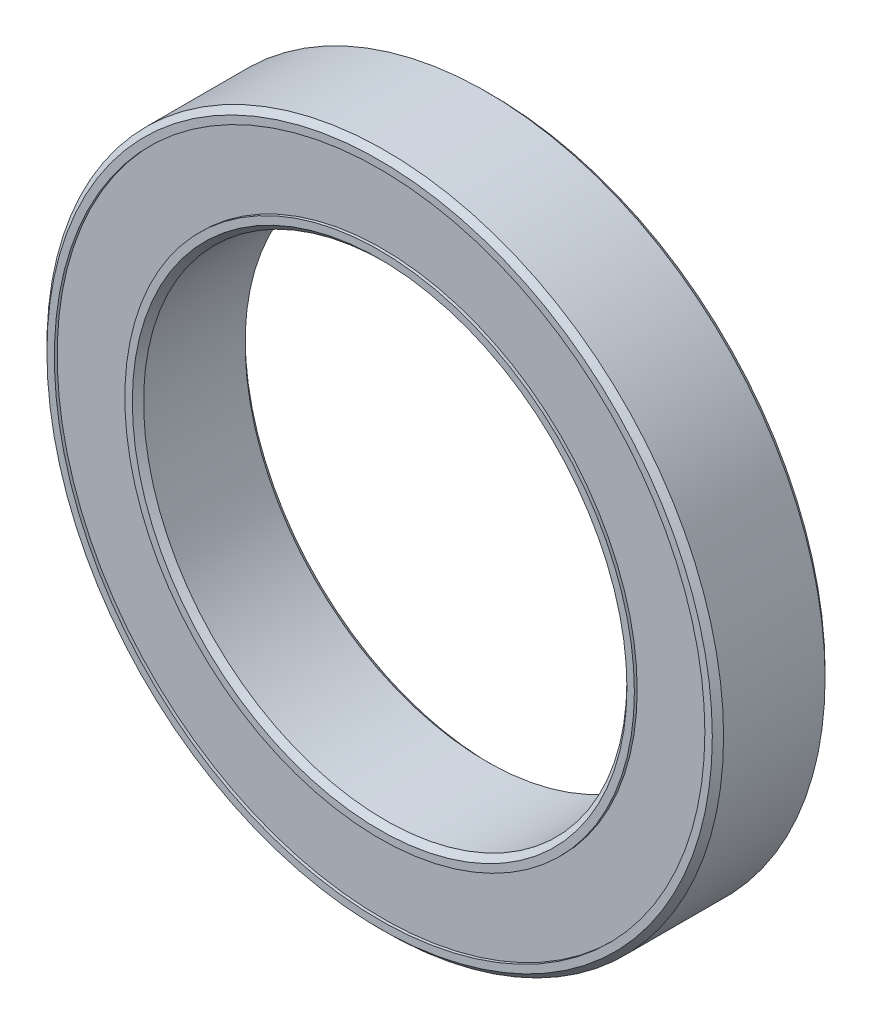
SolidWorks part; units mm, degrees
ref_plane "Front Plane" through (0, 0, 0) normal (0, 0, 1) x (1, 0, 0)
ref_plane "Top Plane" through (0, 0, 0) normal (0, 1, 0) x (1, 0, 0)
ref_plane "Right Plane" through (0, 0, 0) normal (1, 0, 0) x (0, 0, -1)
sketch "Sketch1" plane through (0, 0, 0) normal (0, 0, 1) x (1, 0, 0)
  circle A0 centre (0, 0) radius 21 construction
  circle A1 centre (0, 0) radius 14.9995 construction
  dimension "OD" = 42
  dimension "ID" = 29.999
sketch "Sketch2" plane through (0, 0, 0) normal (1, 0, 0) x (0, 0, -1)
  line L0 (-3.5, 0) -> (3.5, 0) construction
  line L1 (0, 21) -> (0, -21) construction
  line L2 (3.15, 21) -> (-3.15, 21) construction
  line L3 (-3.15, 21) -> (-3.5, 20.65) construction
  line L4 (-3.5, 20.65) -> (-3.5, 20.1872) construction
  line L5 (-3.5, 20.1872) -> (-1.5556, 20.1872) construction
  line L6 (3.5, 20.1872) -> (1.5556, 20.1872) construction
  line L7 (3.5, 20.65) -> (3.5, 20.1872) construction
  line L8 (3.15, 21) -> (3.5, 20.65) construction
  line L9 (0, 21) -> (0, 17.9998) construction
  line L10 (0, 17.9998) -> (0, 14.9995) construction
  line L11 (3.5, 17.9998) -> (-3.5, 17.9998) construction
  line L12 (-3.5, 15.3495) -> (-3.5, 15.8123) construction
  line L13 (-3.15, 14.9995) -> (-3.5, 15.3495) construction
  line L14 (3.15, 14.9995) -> (-3.15, 14.9995) construction
  line L15 (3.15, 14.9995) -> (3.5, 15.3495) construction
  line L16 (3.5, 15.3495) -> (3.5, 15.8123) construction
  line L17 (3.5, 15.8123) -> (1.5556, 15.8123) construction
  line L18 (-3.5, 15.8123) -> (-1.5556, 15.8123) construction
  line L19 (-3.5, 15) -> (-3.5, -15) construction
  line L20 (3.5, 21) -> (3.5, -21) construction
  arc A0 (-1.5556, 20.1872) -> (1.5556, 20.1872) centre (0, 17.9998) cw construction
  arc A1 (-1.5556, 15.8123) -> (1.5556, 15.8123) centre (0, 17.9998) ccw construction
  point P14 (0, 14.9995)
  point P18 (0, 17.9998)
  dimension "Approx. Ball Dia." = 5.3684
  dimension "D1" = 45
  dimension "D2" = 0.35
  dimension "D3" = 3.1111
  dimension "D4" = 2.1875
  dimension "Width" = 7
  dimension "For Shaft Diameter" = 30
  dimension "For Housing ID" = 42
sketch "Sketch3" plane through (0, 0, 0) normal (1, 0, 0) x (0, 0, -1)
  line L0 (-3.5, 20.65) -> (-3.5, 20.1872) construction
  line L1 (-3.15, 21) -> (-3.5, 20.65) construction
  line L2 (3.15, 21) -> (-3.15, 21) construction
  line L3 (3.15, 21) -> (3.5, 20.65) construction
  line L4 (3.5, 20.65) -> (3.5, 20.1872) construction
  line L5 (3.5, 20.1872) -> (1.5556, 20.1872) construction
  line L6 (-3.5, 20.1872) -> (-1.5556, 20.1872) construction
  line L7 (-3.5, 20.65) -> (-3.5, 20.1872)
  line L8 (-3.15, 21) -> (-3.5, 20.65)
  line L9 (3.15, 21) -> (-3.15, 21)
  line L10 (3.15, 21) -> (3.5, 20.65)
  line L11 (3.5, 20.65) -> (3.5, 20.1872)
  line L12 (3.5, 20.1872) -> (1.5556, 20.1872)
  line L13 (-3.5, 20.1872) -> (-1.5556, 20.1872)
  line L14 (-3.5, 15.3495) -> (-3.5, 15.8123) construction
  line L15 (-3.15, 14.9995) -> (-3.5, 15.3495) construction
  line L16 (3.15, 14.9995) -> (-3.15, 14.9995) construction
  line L17 (3.15, 14.9995) -> (3.5, 15.3495) construction
  line L18 (3.5, 15.3495) -> (3.5, 15.8123) construction
  line L19 (3.5, 15.8123) -> (1.5556, 15.8123) construction
  line L20 (-3.5, 15.8123) -> (-1.5556, 15.8123) construction
  line L21 (-3.5, 15.3495) -> (-3.5, 15.8123)
  line L22 (-3.15, 14.9995) -> (-3.5, 15.3495)
  line L23 (3.15, 14.9995) -> (-3.15, 14.9995)
  line L24 (3.15, 14.9995) -> (3.5, 15.3495)
  line L25 (3.5, 15.3495) -> (3.5, 15.8123)
  line L26 (3.5, 15.8123) -> (1.5556, 15.8123)
  line L27 (-3.5, 15.8123) -> (-1.5556, 15.8123)
  arc A0 (1.5556, 20.1872) -> (-1.5556, 20.1872) centre (0, 17.9998) ccw construction
  arc A1 (1.5556, 20.1872) -> (-1.5556, 20.1872) centre (0, 17.9998) ccw
  arc A2 (-1.5556, 15.8123) -> (1.5556, 15.8123) centre (0, 17.9998) ccw construction
  arc A3 (-1.5556, 15.8123) -> (1.5556, 15.8123) centre (0, 17.9998) ccw
revolve "Revolve1" add sketch "Sketch3" angle 360 about L0
sketch "Sketch4" plane through (0, 0, 0) normal (1, 0, 0) x (0, 0, -1)
  line L0 (-2.6842, 17.9998) -> (2.6842, 17.9998)
  arc A2 (-2.6842, 17.9998) -> (2.6842, 17.9998) centre (0, 17.9998) cw
  arc A3 (1.5556, 20.1872) -> (-1.5556, 20.1872) centre (0, 17.9998) ccw construction
revolve "Revolve2" add sketch "Sketch4" angle 360 about L0
pattern_circular "CirPattern1" count 12 over 360 about axis through (0, 0, 0) along (0, 0, 1) of bodies 104
sketch "Sketch5" plane through (0, 0, 0) normal (1, 0, 0) x (0, 0, -1)
  line L0 (-3.5, 20.1872) -> (-1.5556, 20.1872) construction
  line L1 (-3.325, 20.1872) -> (-2.6842, 20.1872)
  line L2 (-3.325, 20.1872) -> (-3.325, 15.8123)
  line L3 (-3.325, 15.8123) -> (-2.6842, 15.8123)
  line L4 (-2.6842, 20.1872) -> (-2.6842, 15.8123)
  line L6 (3.5, 20.1872) -> (1.5556, 20.1872) construction
  line L7 (3.325, 20.1872) -> (2.6842, 20.1872)
  line L8 (3.325, 20.1872) -> (3.325, 15.8123)
  line L9 (3.325, 15.8123) -> (2.6842, 15.8123)
  line L10 (2.6842, 20.1872) -> (2.6842, 15.8123)
  line L12 (-3.15, 21) -> (-3.5, 20.65) construction
  line L13 (-3.5, 15.8123) -> (-1.5556, 15.8123) construction
  line L14 (3.5, 15.8123) -> (1.5556, 15.8123) construction
  point P18 (-3.325, 20.825)
revolve "Revolve3" add sketch "Sketch5" angle 360 about L0
equation "\"D2@Sketch2\"= \"Width@Sketch2\" * .05"
equation "\"D3@Sketch2\"=\"Width@Sketch2\" / 2.25"
equation "\"D4@Sketch2\"=( \"OD@Sketch1\" - \"Width@Sketch2\" ) *.5 *.125"
equation "\"Approx. No. of Balls\"= ( pi * \"OD@Sketch1\" ) * .5 / \"Approx. Ball Dia.@Sketch2\""
equation "\"Balls@CirPattern1\"=\"Approx. No. of Balls\""
